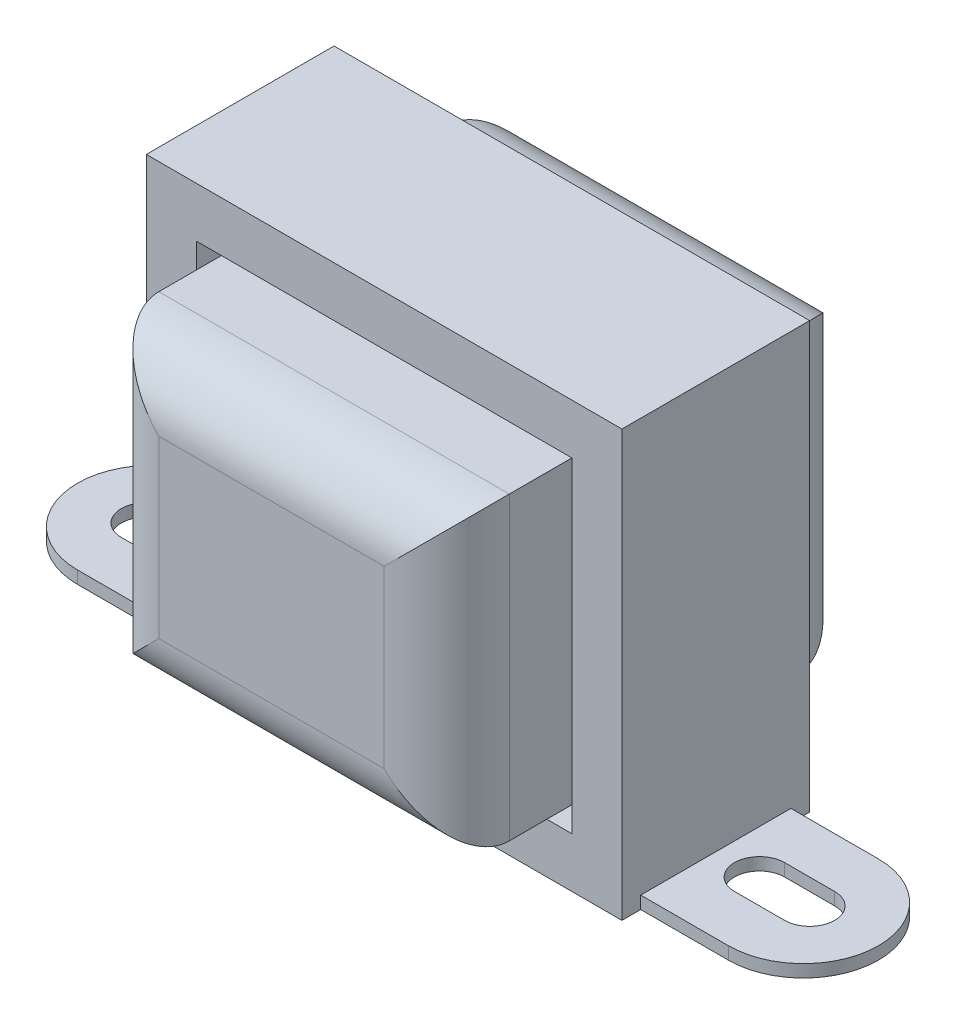
SolidWorks part; units mm, degrees
ref_plane "Front Plane" through (0, 0, 0) normal (0, 0, 1) x (1, 0, 0)
ref_plane "Top Plane" through (0, 0, 0) normal (0, 1, 0) x (1, 0, 0)
ref_plane "Right Plane" through (0, 0, 0) normal (1, 0, 0) x (0, 0, -1)
sketch "Sketch1" plane through (0, 0, 0) normal (0, 0, 1) x (1, 0, 0)
  line L1 (-19, 17) -> (19, 17)
  line L2 (-19, 17) -> (-19, -17)
  line L3 (-19, -17) -> (19, -17)
  line L4 (19, 17) -> (19, -17)
  line L5 (-19, 17) -> (19, -17) construction
  line L6 (-19, -17) -> (19, 17) construction
  point P0 (0, 0)
  dimension "D1" = 34
  dimension "D2" = 38
extrude "Boss-Extrude1" add sketch "Sketch1" along normal mid plane 15
sketch "Sketch2" plane through (0, -17, 0) normal (0, -1, 0) x (1, 0, 0)
  line L0 (-19, 0) -> (-26, 0) construction
  line L1 (-19, 7.5) -> (-19, -7.5) construction
  line L2 (-19, -6) -> (-26, -6)
  line L3 (-19, 6) -> (-26, 6)
  line L4 (0, -55) -> (0, 55) construction
  line L5 (19, 0) -> (26, 0) construction
  line L6 (19, -6) -> (26, -6)
  line L7 (19, 6) -> (26, 6)
  line L8 (-19, 6) -> (-19, -6)
  arc A0 (-19, -6) -> (-19, 6) centre (-19, 0) ccw
  arc A1 (-26, 6) -> (-26, -6) centre (-26, 0) ccw
  arc A2 (19, -6) -> (19, 6) centre (19, 0) cw
  arc A3 (26, 6) -> (26, -6) centre (26, 0) cw
  point P5 (-22.5, 0)
  point P15 (22.5, 0)
  line M11 (19, -7.5) -> (19, 7.5)
  line M13 (-19, 7.5) -> (-19, -7.5)
  dimension "D1" = 6
  dimension "D2" = 7
extrude "Boss-Extrude2" add sketch "Sketch2" against normal blind 1 contours A3 L7 L6 M11 | L3 A1 L2 M13
sketch "Sketch3" plane through (0, -16, 0) normal (0, 1, 0) x (1, 0, 0)
  line L0 (-22.4956, 0) -> (-26.4956, 0) construction
  line L1 (-22.4956, -2) -> (-26.4956, -2)
  line L2 (-22.4956, 2) -> (-26.4956, 2)
  line L3 (-55, 0) -> (55, 0) construction
  line L4 (-19, -6) -> (-19, 6) construction
  line L5 (0, -55) -> (0, 55) construction
  line L6 (22.4956, 0) -> (26.4956, 0) construction
  line L7 (22.4956, -2) -> (26.4956, -2)
  line L8 (22.4956, 2) -> (26.4956, 2)
  arc A0 (-22.4956, -2) -> (-22.4956, 2) centre (-22.4956, 0) ccw
  arc A1 (-26.4956, 2) -> (-26.4956, -2) centre (-26.4956, 0) ccw
  arc A2 (22.4956, -2) -> (22.4956, 2) centre (22.4956, 0) cw
  arc A3 (26.4956, 2) -> (26.4956, -2) centre (26.4956, 0) cw
  point P3 (-24.4956, 0)
  point P18 (24.4956, 0)
  dimension "D1" = 2
  dimension "D2" = 4
  dimension "D3" = 5.4956
extrude "Cut-Extrude1" cut sketch "Sketch3" against normal up to next
sketch "Sketch4" plane through (0, 0, -7.5) normal (0, 0, -1) x (-1, 0, 0)
  line L1 (15, -13) -> (-15, -13)
  line L2 (15, -13) -> (15, 13)
  line L3 (15, 13) -> (-15, 13)
  line L4 (-15, -13) -> (-15, 13)
  line L5 (15, -13) -> (-15, 13) construction
  line L6 (15, 13) -> (-15, -13) construction
  point P0 (0, 0)
  dimension "D1" = 30
  dimension "D2" = 26
extrude "Cut-Extrude2" cut sketch "Sketch4" against normal up to next
sketch "Sketch5" plane through (0, 0, 0) normal (0, 0, 1) x (1, 0, 0)
  line L1 (-14, 12) -> (14, 12)
  line L2 (-14, 12) -> (-14, -12)
  line L3 (-14, -12) -> (14, -12)
  line L4 (14, 12) -> (14, -12)
  line L5 (-14, 12) -> (14, -12) construction
  line L6 (-14, -12) -> (14, 12) construction
  point P0 (0, 0)
  dimension "D1" = 24
  dimension "D2" = 28
extrude "Boss-Extrude3" add sketch "Sketch5" along normal mid plane 33 separate body
fillet "Fillet1" radius 5 8 edges at (0, 12, -16.5) (-14, 0, -16.5) (0, -12, -16.5) (14, 0, -16.5) (0, -12, 16.5) (-14, 0, 16.5) (0, 12, 16.5) (14, 0, 16.5)
